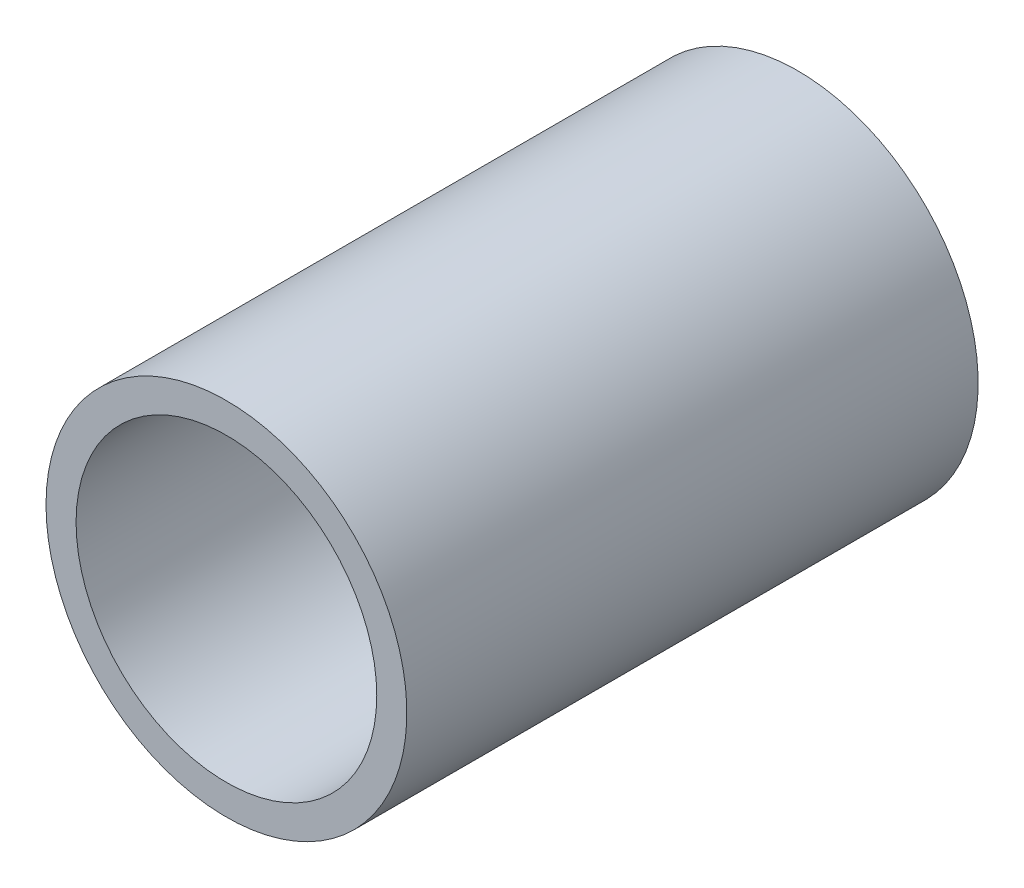
SolidWorks part; units mm, degrees
material "6061-T6 (SS)"
ref_plane "Front Plane" through (0, 0, 0) normal (0, 0, 1) x (1, 0, 0)
ref_plane "Top Plane" through (0, 0, 0) normal (0, 1, 0) x (1, 0, 0)
ref_plane "Right Plane" through (0, 0, 0) normal (1, 0, 0) x (0, 0, -1)
sketch "Sketch1" plane through (0, 0, 0) normal (0, 0, 1) x (1, 0, 0)
  line L1 (7.3323, 0) -> (3.6662, 6.35) construction
  line L2 (3.6662, 6.35) -> (-3.6662, 6.35) construction
  line L3 (-3.6662, 6.35) -> (-7.3323, 0) construction
  line L4 (-7.3323, 0) -> (-3.6662, -6.35) construction
  line L5 (-3.6662, -6.35) -> (3.6662, -6.35) construction
  line L6 (3.6662, -6.35) -> (7.3323, 0) construction
  circle A0 centre (0, 0) radius 6.35 construction
  circle A1 centre (0, 0) radius 7.9375
  circle A2 centre (0, 0) radius 9.525
  dimension "D2" = 15.875
  dimension "D3" = 19.05
  dimension "D1" = 12.7
extrude "Boss-Extrude1" add sketch "Sketch1" along normal blind 30.1625
